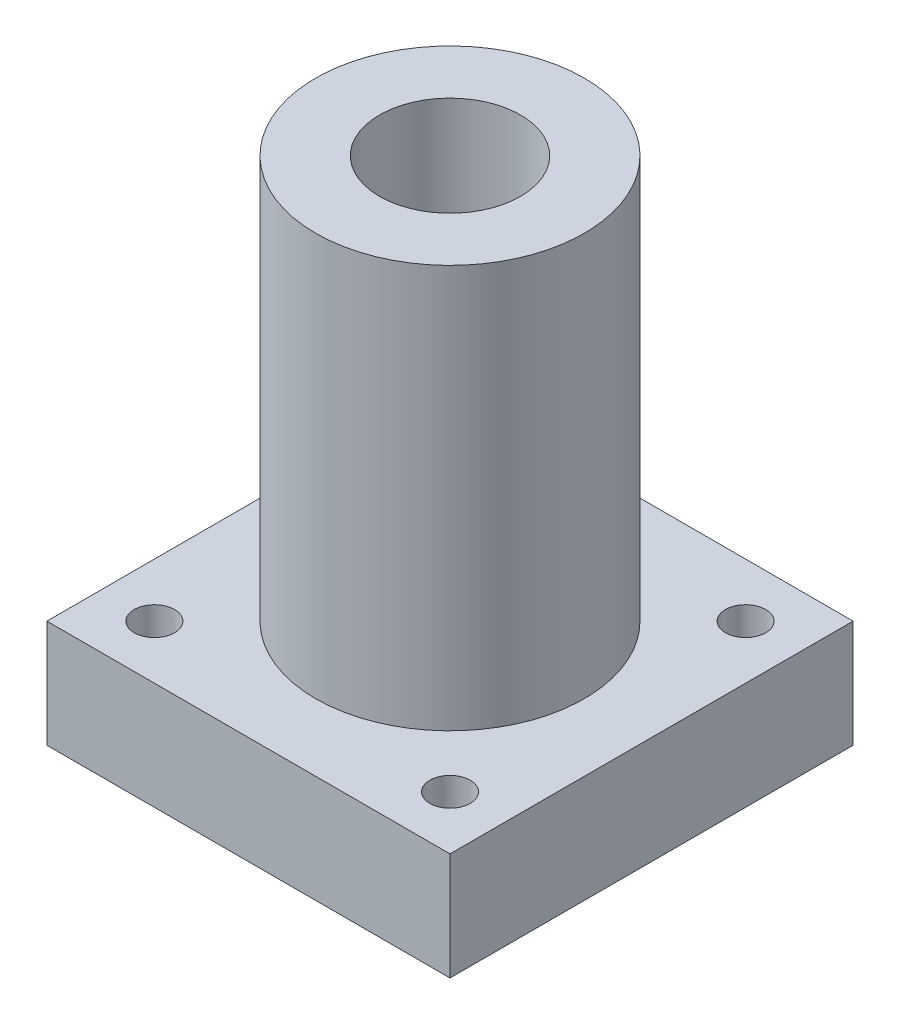
SolidWorks part; units mm, degrees
ref_plane "Ön Düzlem" through (0, 0, 0) normal (0, 0, 1) x (1, 0, 0)
ref_plane "Üst Düzlem" through (0, 0, 0) normal (0, 1, 0) x (1, 0, 0)
ref_plane "Sağ Düzlem" through (0, 0, 0) normal (1, 0, 0) x (0, 0, -1)
sketch "Çizim1" plane through (0, 0, 0) normal (0, 1, 0) x (1, 0, 0)
  line L1 (0, 0) -> (30, 0)
  line L2 (0, 0) -> (0, 30)
  line L3 (0, 30) -> (30, 30)
  line L4 (30, 0) -> (30, 30)
  dimension "D1" = 30
extrude "Yükseklik-Ekstrüzyon1" add sketch "Çizim1" along normal blind 40
sketch "Çizim2" plane through (0, 40, 0) normal (0, 1, 0) x (1, 0, 0)
  line L0 (30, 30) -> (0, 30) construction
  line L1 (0, 30) -> (0, 0) construction
  line L2 (30, 0) -> (30, 30) construction
  line L3 (0, 0) -> (30, 0) construction
  circle A0 centre (4, 26) radius 1.5
  circle A1 centre (26, 26) radius 1.5
  circle A2 centre (26, 4) radius 1.5
  circle A3 centre (4, 4) radius 1.5
  dimension "D1" = 3
  dimension "D2" = 4
  dimension "D4" = 4
  dimension "D5" = 4
  dimension "D3" = 4
extrude "Kes-Ekstrüzyon1" cut sketch "Çizim2" against normal blind 40
sketch "Çizim3" plane through (0, 40, 0) normal (0, 1, 0) x (1, 0, 0)
  line L0 (30, 0) -> (30, 30) construction
  line L1 (30, 30) -> (0, 30) construction
  circle A0 centre (15, 15) radius 10
  circle A1 centre (15, 15) radius 5.25
  dimension "D1" = 20
  dimension "D2" = 10.5
  dimension "D3" = 15
  dimension "D4" = 15
extrude "Yükseklik-Ekstrüzyon2" add sketch "Çizim3" along normal blind 40
sketch "Çizim4" plane through (0, 0, 0) normal (0, -1, 0) x (1, 0, 0)
  line L1 (0, -30) -> (30, -30)
  line L2 (0, -30) -> (0, 0)
  line L3 (0, 0) -> (30, 0)
  line L4 (30, -30) -> (30, 0)
extrude "Kes-Ekstrüzyon2" cut sketch "Çizim4" against normal blind 32
sketch "Çizim5" plane through (0, 80, 0) normal (0, 1, 0) x (1, 0, 0)
  circle A0 centre (15, 15) radius 10
extrude "Kes-Ekstrüzyon3" cut sketch "Çizim5" against normal blind 10
sketch "Çizim6" plane through (0, 40, 0) normal (0, 1, 0) x (1, 0, 0)
  circle A0 centre (15, 15) radius 5.25
  circle A1 centre (15, 15) radius 5.25 construction
extrude "Kes-Ekstrüzyon4" cut sketch "Çizim6" against normal blind 30
